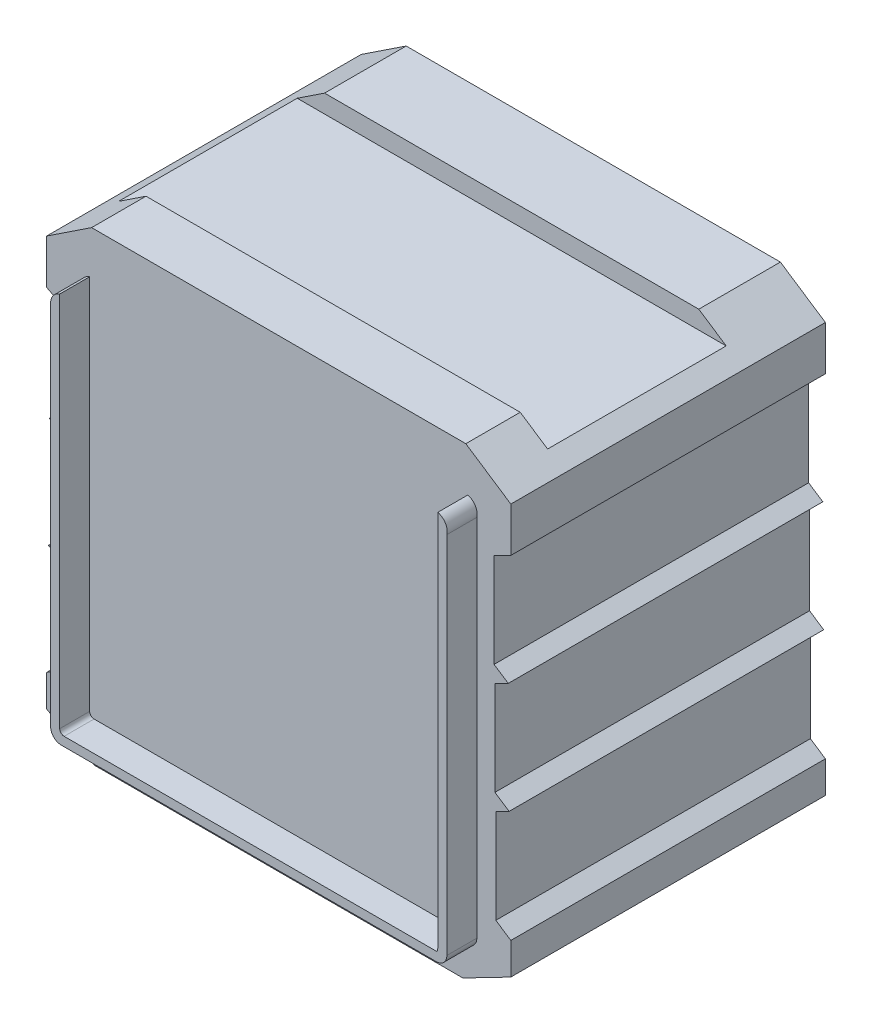
SolidWorks part; units mm, degrees
material "1060 Alloy"
ref_plane "Front" through (0, 0, 0) normal (0, 0, 1) x (1, 0, 0)
ref_plane "Top" through (0, 0, 0) normal (0, 1, 0) x (1, 0, 0)
ref_plane "Right" through (0, 0, 0) normal (1, 0, 0) x (0, 0, -1)
sketch "Sketch1" plane through (0, 0, 0) normal (0, 0, 1) x (1, 0, 0)
  line L0 (-103.1895, 0) -> (103.1895, 0)
  line L1 (103.1895, 0) -> (128, -16.4326)
  line L2 (128, -16.4326) -> (128, -40.963)
  line L3 (128, -40.963) -> (118.7742, -45.6193)
  line L4 (118.7742, -45.6193) -> (118.7742, -97.6193)
  line L5 (118.7742, -97.6193) -> (126.5833, -102.7916)
  line L6 (126.5833, -102.7916) -> (119.254, -106.4908)
  line L7 (119.254, -106.4908) -> (119.254, -158.4908)
  line L8 (119.254, -158.4908) -> (127.0632, -163.663)
  line L9 (127.0632, -163.663) -> (119.7339, -167.3622)
  line L10 (119.7339, -167.3622) -> (119.7339, -219.3622)
  line L11 (119.7339, -219.3622) -> (128, -224.837)
  line L12 (128, -224.837) -> (128, -242.3453)
  line L13 (128, -242.3453) -> (101.5588, -256)
  line L14 (101.5588, -256) -> (-101.5588, -256)
  line L15 (0, 0) -> (0, -256) construction
  line L16 (-128, -242.3453) -> (-101.5588, -256)
  line L17 (-128, -224.837) -> (-128, -242.3453)
  line L18 (-119.7339, -219.3622) -> (-128, -224.837)
  line L19 (-119.7339, -167.3622) -> (-119.7339, -219.3622)
  line L20 (-127.0632, -163.663) -> (-119.7339, -167.3622)
  line L21 (-119.254, -158.4908) -> (-127.0632, -163.663)
  line L22 (-119.254, -106.4908) -> (-119.254, -158.4908)
  line L23 (-126.5833, -102.7916) -> (-119.254, -106.4908)
  line L24 (-118.7742, -97.6193) -> (-126.5833, -102.7916)
  line L25 (-118.7742, -45.6193) -> (-118.7742, -97.6193)
  line L26 (-128, -40.963) -> (-118.7742, -45.6193)
  line L27 (-128, -16.4326) -> (-128, -40.963)
  line L28 (-103.1895, 0) -> (-128, -16.4326)
  point P17 (128.9716, -232.6306)
  point P18 (120.5518, -141.3643)
  point P19 (120.5518, -151.3515)
  point P20 (128, -142.8439)
  point P21 (129.5476, -245.3044)
  point P22 (0, 0)
  point P23 (0, 0)
  point P24 (124.739, -242.3453)
  dimension "D1" = 256
  dimension "D2" = 52
  dimension "D3" = 52
  dimension "D4" = 52
  dimension "D5" = 256
extrude "Boss-Extrude1" add sketch "Sketch1" along normal blind 173.478
sketch "Sketch3" plane through (0, 0, 173.478) normal (0, 0, 1) x (1, 0, 0)
  line L0 (-109.254, -30.7764) -> (-109.254, -233.135)
  line L1 (-103.389, -239) -> (103.389, -239)
  line L2 (109.254, -233.135) -> (109.254, -32.174)
  line L3 (104.254, -23.9952) -> (104.254, -231.7845)
  line L4 (103.7898, -234) -> (-101.83, -234)
  line L5 (-104.254, -231.576) -> (-104.254, -23.9952)
  line L6 (119.254, -158.4908) -> (119.254, -106.4908) construction
  line L7 (-119.254, -106.4908) -> (-119.254, -158.4908) construction
  line L8 (-101.5588, -256) -> (101.5588, -256) construction
  arc A0 (-109.254, -233.135) -> (-103.389, -239) centre (-103.389, -233.135) ccw
  arc A1 (103.389, -239) -> (109.254, -233.135) centre (103.389, -233.135) ccw
  arc A3 (104.254, -231.7845) -> (103.7898, -234) centre (98.7346, -231.7845) cw
  arc A4 (-101.83, -234) -> (-104.254, -231.576) centre (-101.83, -231.576) cw
  arc A5 (-109.254, -30.7764) -> (-104.254, -23.9952) centre (-102.1556, -30.7764) cw
  arc A6 (109.254, -32.174) -> (104.254, -23.9952) centre (102.6646, -30.5846) ccw
  dimension "D1" = 10
  dimension "D2" = 10
  dimension "D3" = 5
  dimension "D4" = 5
  dimension "D5" = 5
  dimension "D6" = 17
extrude "Boss-Extrude2" add sketch "Sketch3" along normal blind 16.522
sketch "Sketch5" plane through (0, 0, 0) normal (0, 1, 0) x (1, 0, 0)
  line L0 (-128, -173.478) -> (-128, 0) construction
  line L1 (-128, -143.478) -> (128, -143.478)
  line L2 (-128, -143.478) -> (-128, -45)
  line L3 (-128, -45) -> (128, -45)
  line L4 (128, -143.478) -> (128, -45)
  line L5 (128, -173.478) -> (128, 0) construction
  line L7 (103.7898, -173.478) -> (-101.83, -173.478) construction
  line L8 (103.1895, 0) -> (-103.1895, 0) construction
  dimension "D1" = 30
  dimension "D2" = 45
extrude "Cut-Extrude3" cut sketch "Sketch5" against normal blind 10
sketch "Sketch6" plane through (0, 0, 173.478) normal (0, 0, 1) x (1, 0, 0)
  line L0 (-17.4423, -269.8438) -> (292.5577, -269.8438) construction
